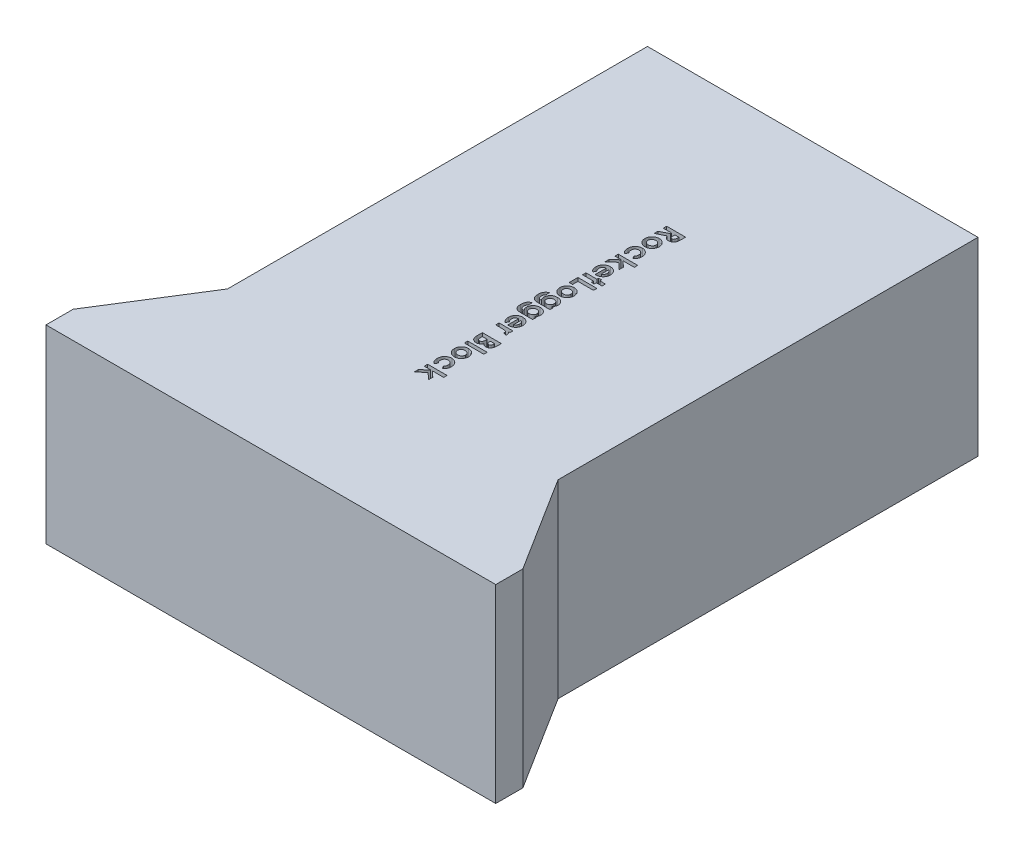
SolidWorks part; units mm, degrees
ref_plane "Front Plane" through (0, 0, 0) normal (0, 0, 1) x (1, 0, 0)
ref_plane "Top Plane" through (0, 0, 0) normal (0, 1, 0) x (1, 0, 0)
ref_plane "Right Plane" through (0, 0, 0) normal (1, 0, 0) x (0, 0, -1)
sketch "Sketch1" plane through (0, 0, 0) normal (0, 1, 0) x (1, 0, 0)
  line L0 (-41.5, 0) -> (41.5, 0)
  line L2 (30.5, 22.5) -> (30.5, 100)
  line L3 (30.5, 100) -> (-30.5, 100)
  line L4 (-30.5, 100) -> (-30.5, 22.5)
  line L6 (-30.5, 22.5) -> (30.5, 22.5) construction
  line L7 (0, 100) -> (0, 0) construction
  line L8 (-41.5, 0) -> (-41.5, 5)
  line L9 (-41.5, 5) -> (-30.5, 22.5)
  line L10 (41.5, 0) -> (41.5, 5)
  line L11 (41.5, 5) -> (30.5, 22.5)
  point P11 (0, 0)
  dimension "D1" = 83
  dimension "D2" = 100
  dimension "D3" = 61
  dimension "D4" = 0
  dimension "D5" = 0
  dimension "D6" = 45
  dimension "D7" = 5
  dimension "D8" = 5
extrude "Boss-Extrude1" add sketch "Sketch1" along normal blind 35
sketch "Sketch2" plane through (0, 35, 0) normal (0, 1, 0) x (1, 0, 0)
  line L0 (0, 100) -> (0, 0) construction
  line L1 (30.5, 100) -> (-30.5, 100) construction
  text T0 "<b>RocketLogger Block</b>"
extrude "Cut-Extrude1" cut sketch "Sketch2" against normal blind 5
